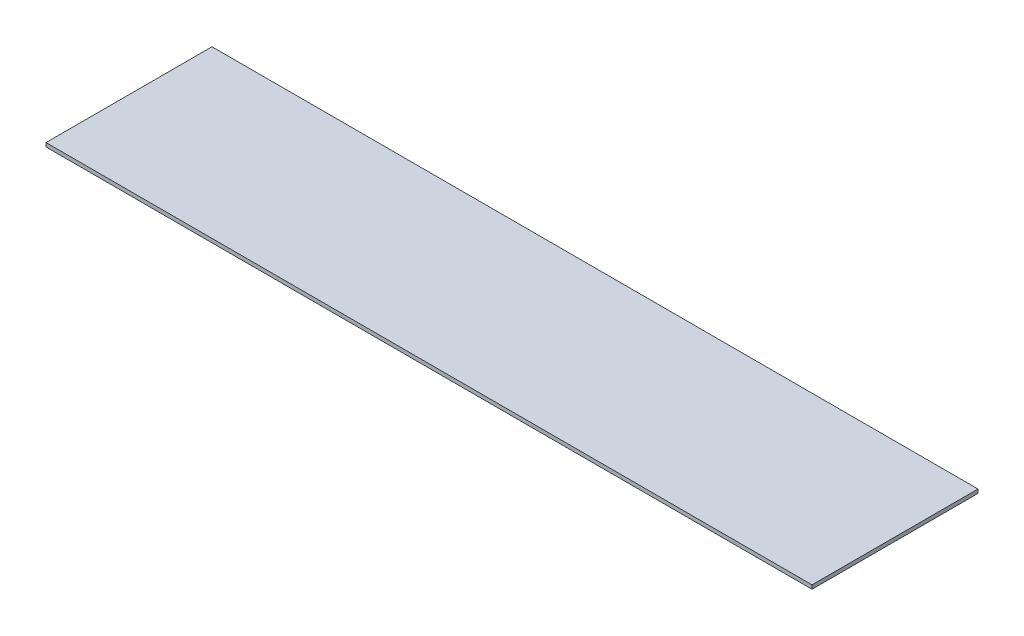
SolidWorks part; units mm, degrees
material "Chapa F.F 1020 - 1,5 mm"
ref_plane "Plano frontal" through (0, 0, 0) normal (0, 0, 1) x (1, 0, 0)
ref_plane "Plano superior" through (0, 0, 0) normal (0, 1, 0) x (1, 0, 0)
ref_plane "Plano direito" through (0, 0, 0) normal (1, 0, 0) x (0, 0, -1)
sketch "Esboço1" plane through (0, 0, 0) normal (0, 1, 0) x (1, 0, 0)
  line L1 (0, 0) -> (300, 0)
  line L2 (0, 0) -> (0, 65)
  line L3 (0, 65) -> (300, 65)
  line L4 (300, 0) -> (300, 65)
  dimension "D1" = 300
  dimension "D2" = 65
extrude "Ressalto-extrusão1" add sketch "Esboço1" along normal blind 1.5
